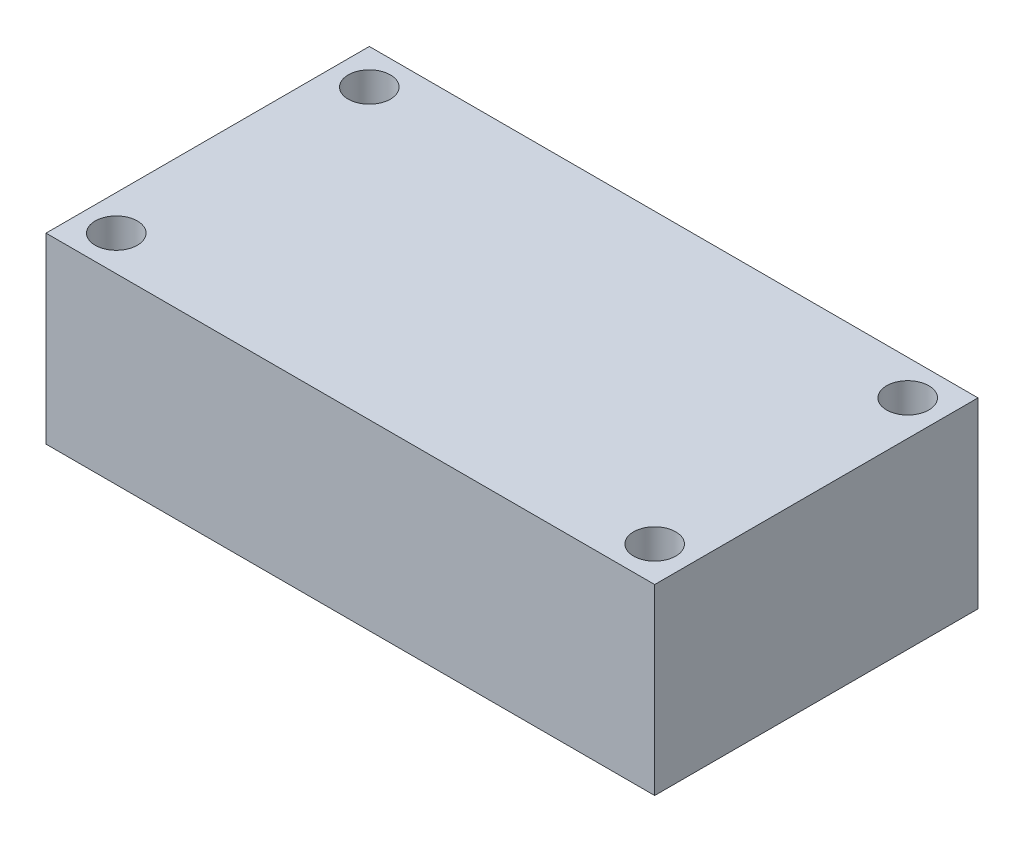
SolidWorks part; units mm, degrees
ref_plane "Płaszczyzna przednia" through (0, 0, 0) normal (0, 0, 1) x (1, 0, 0)
ref_plane "Płaszczyzna górna" through (0, 0, 0) normal (0, 1, 0) x (1, 0, 0)
ref_plane "Płaszczyzna prawa" through (0, 0, 0) normal (1, 0, 0) x (0, 0, -1)
sketch "Szkic1" plane through (0, 0, 0) normal (0, 1, 0) x (1, 0, 0)
  line L1 (0, 0) -> (43.3, 0)
  line L2 (0, 0) -> (0, 23)
  line L3 (0, 23) -> (43.3, 23)
  line L4 (43.3, 0) -> (43.3, 23)
  line L6 (0, 0) -> (0, 2.5)
  circle A0 centre (2.5, 20.5) radius 1.5
  circle A1 centre (2.5, 2.5) radius 1.5
  circle A2 centre (40.8, 2.5) radius 1.5
  circle A3 centre (40.8, 20.5) radius 1.5
extrude "Dodanie-wyciągnięcie1" add sketch "Szkic1" along normal blind 13 contours L1 L4 L3 L2 A2 A1 A0 A3
